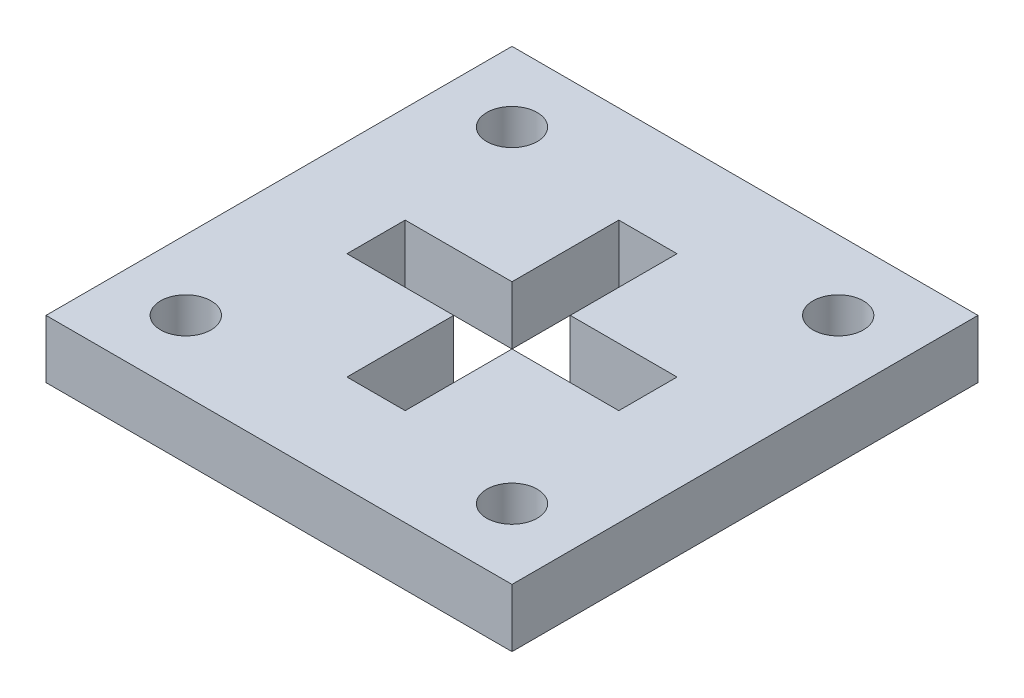
SolidWorks part; units mm, degrees
ref_plane "Front Plane" through (0, 0, 0) normal (0, 0, 1) x (1, 0, 0)
ref_plane "Top Plane" through (0, 0, 0) normal (0, 1, 0) x (1, 0, 0)
ref_plane "Right Plane" through (0, 0, 0) normal (1, 0, 0) x (0, 0, -1)
sketch "Sketch1" plane through (0, 0, 0) normal (0, 1, 0) x (1, 0, 0)
  line L1 (0, 0) -> (50.8, 0)
  line L2 (0, 0) -> (0, 50.8)
  line L3 (0, 50.8) -> (50.8, 50.8)
  line L4 (50.8, 0) -> (50.8, 50.8)
  line L5 (25.4, 50.8) -> (25.4, 0) construction
  line L6 (0, 25.4) -> (50.8, 25.4) construction
  point P80 (25.4, 25.4)
  dimension "D1" = 50.8
extrude "Boss-Extrude1" add sketch "Sketch1" along normal blind 6.35
sketch "Sketch2" plane through (0, 6.35, 0) normal (0, 1, 0) x (1, 0, 0)
  line L0 (10.5833, 50.8) -> (10.5833, 0) construction
  line L3 (50.8, 50.8) -> (0, 50.8) construction
  line L11 (0, 0) -> (50.8, 0) construction
  line L12 (0, 50.8) -> (0, 0) construction
  line L17 (0, 10.5833) -> (50.8, 10.5833) construction
  line L18 (50.8, 0) -> (50.8, 50.8) construction
  line L22 (40.2167, 50.8) -> (40.2167, 0) construction
  line L23 (0, 40.2167) -> (50.8, 40.2167) construction
  line L24 (25.4, 40.2167) -> (25.4, 10.5833) construction
  line L25 (10.5833, 25.4) -> (40.2167, 25.4) construction
  line L26 (28.575, 28.575) -> (40.2167, 28.575)
  line L27 (22.225, 40.2167) -> (28.575, 40.2167)
  line L28 (22.225, 40.2167) -> (22.225, 28.575)
  line L29 (22.225, 10.5833) -> (28.575, 10.5833)
  line L30 (28.575, 40.2167) -> (28.575, 28.575)
  line L31 (25.4, 10.5833) -> (25.4, 40.2167) construction
  line L32 (22.225, 25.4) -> (28.575, 25.4) construction
  line L33 (10.5833, 28.575) -> (22.225, 28.575)
  line L34 (10.5833, 28.575) -> (10.5833, 22.225)
  line L35 (10.5833, 22.225) -> (22.225, 22.225)
  line L36 (40.2167, 28.575) -> (40.2167, 22.225)
  line L37 (25.4, 22.225) -> (25.4, 28.575) construction
  line L38 (10.5833, 25.4) -> (40.2167, 25.4) construction
  line L39 (28.575, 22.225) -> (40.2167, 22.225)
  line L40 (28.575, 22.225) -> (28.575, 10.5833)
  line L41 (22.225, 22.225) -> (22.225, 10.5833)
  point P240 (25.4, 25.4)
  point P531 (25.4, 25.4)
  dimension "D1" = 10.5833
  dimension "D2" = 10.5833
  dimension "D3" = 10.5833
  dimension "D4" = 10.5833
  dimension "D5" = 6.35
  dimension "D6" = 6.35
extrude "Cut-Extrude1" cut sketch "Sketch2" against normal blind 6.35
sketch "Sketch5" plane through (0, 6.35, 0) normal (0, 1, 0) x (1, 0, 0)
  line L0 (7.62, 43.18) -> (7.62, 7.62) construction
  line L1 (0, 50.8) -> (50.8, 50.8) construction
  line L2 (0, 50.8) -> (0, 0) construction
  line L3 (0, 0) -> (50.8, 0) construction
  line L4 (50.8, 50.8) -> (50.8, 0) construction
  line L5 (7.62, 7.62) -> (43.18, 7.62) construction
  line L6 (43.18, 43.18) -> (43.18, 7.62) construction
  line L7 (7.62, 43.18) -> (43.18, 43.18) construction
  dimension "D1" = 7.62
hole_wizard "M5 Clearance Hole1" positions "Sketch6" profile "Sketch8" hole size "M5" standard "ANSI Metric" end condition through all
sketch "Sketch6" plane through (0, 6.35, 0) normal (0, 1, 0) x (1, 0, 0)
  point P0 (7.62, 43.18)
  point P3 (43.18, 43.18)
  point P6 (43.18, 7.62)
  point P9 (7.62, 7.62)
sketch "Sketch8" plane through (7.62, 6.35, -43.18) normal (1, 0, 0) x (0, 0, 1)
  line L0 (0, 0) -> (0, 6.35)
  line L1 (0, 6.35) -> (2.75, 6.35)
  line L2 (2.75, 6.35) -> (2.75, 0)
  line L5 (2.75, 0) -> (0, 0)
  line L11 (0, -6.35) -> (0, 107.95) construction
  dimension "Thru Hole Dia." = 5.5
  dimension "Thru Hole Depth" = 6.35
equation "\"Stock Thickness\"= .25in"
equation "\"D1@Boss-Extrude1\"=\"Stock Thickness\""
equation "\"D1@Cut-Extrude1\"=\"Stock Thickness\""
equation "\"D1@Sketch2\"=\"D1@Sketch1\"/3 - \"Stock Thickness\""
equation "\"D2@Sketch2\"=\"D1@Sketch1\"/3 - \"Stock Thickness\""
equation "\"D3@Sketch2\"=\"D2@Sketch2\""
equation "\"D4@Sketch2\"=\"D1@Sketch2\""
equation "\"D5@Sketch2\"=\"Stock Thickness\""
equation "\"D6@Sketch2\"=\"Stock Thickness\""
